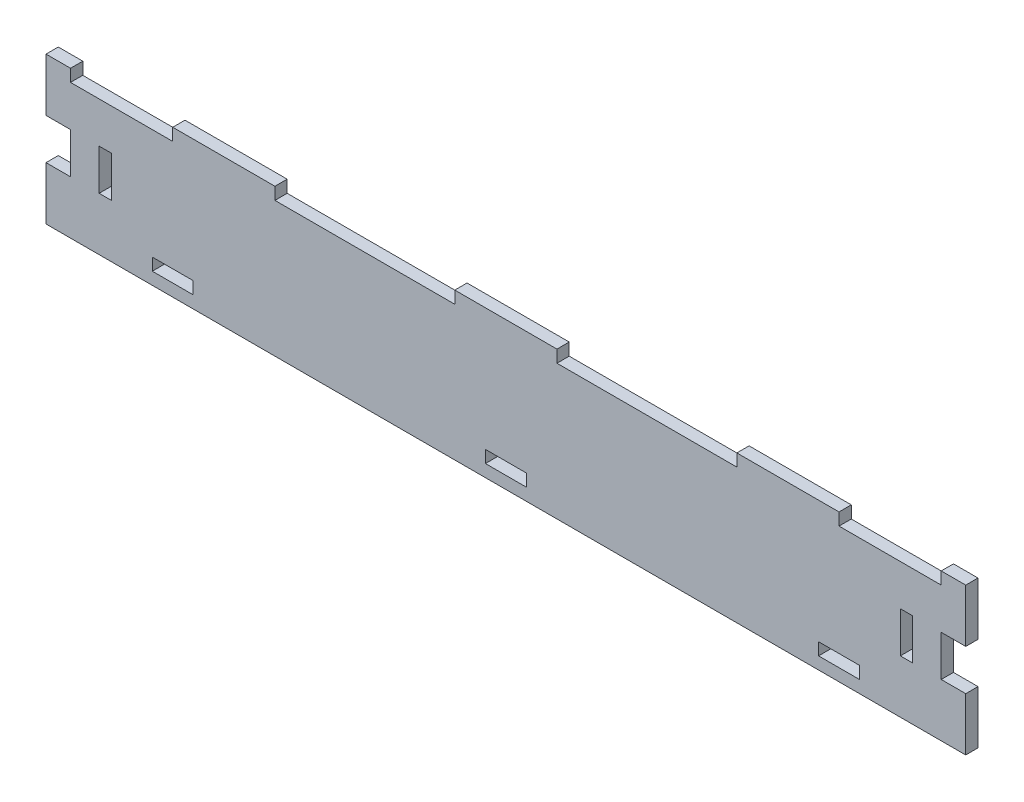
SolidWorks part; units mm, degrees
ref_plane "Спереди" through (0, 0, 0) normal (0, 0, 1) x (1, 0, 0)
ref_plane "Сверху" through (0, 0, 0) normal (0, 1, 0) x (1, 0, 0)
ref_plane "Справа" through (0, 0, 0) normal (1, 0, 0) x (0, 0, -1)
sketch "Эскиз1" plane through (0, 0, 0) normal (0, 0, 1) x (1, 0, 0)
  line L0 (0, 60) -> (0, 66)
  line L1 (0, 0) -> (450, 0) construction
  line L2 (0, 0) -> (0, 20)
  line L3 (12, 60) -> (62, 60)
  line L4 (450, 0) -> (450, 20)
  line L5 (0, 66) -> (12, 66)
  line L6 (12, 66) -> (12, 60)
  line L7 (62, 60) -> (62, 66)
  line L8 (62, 66) -> (112, 66)
  line L9 (112, 66) -> (112, 60)
  line L10 (200, 60) -> (200, 66)
  line L11 (200, 66) -> (250, 66)
  line L12 (250, 66) -> (250, 60)
  line L13 (338, 60) -> (338, 66)
  line L14 (338, 66) -> (388, 66)
  line L15 (388, 66) -> (388, 60)
  line L16 (438, 60) -> (438, 66)
  line L17 (438, 66) -> (450, 66)
  line L18 (450, 66) -> (450, 60)
  line L19 (0, 66) -> (450, 66) construction
  line L20 (112, 60) -> (200, 60)
  line L21 (250, 60) -> (338, 60)
  line L22 (388, 60) -> (438, 60)
  line L23 (0, 60) -> (450, 60) construction
  line L24 (52, 0) -> (52, 6)
  line L25 (52, 6) -> (72, 6)
  line L26 (72, 6) -> (72, 0)
  line L27 (215, 0) -> (215, 6)
  line L28 (215, 6) -> (235, 6)
  line L29 (235, 6) -> (235, 0)
  line L31 (378, 0) -> (378, 6)
  line L32 (378, 6) -> (398, 6)
  line L33 (398, 6) -> (398, 0)
  line L37 (-1058.3662, 6) -> (0, 6) construction
  line L38 (0, 20) -> (12, 20)
  line L39 (12, 20) -> (12, 40)
  line L40 (12, 40) -> (0, 40)
  line L41 (450, 20) -> (438, 20)
  line L42 (26, 20) -> (32, 20)
  line L43 (26, 20) -> (26, 40)
  line L44 (26, 40) -> (32, 40)
  line L45 (32, 20) -> (32, 40)
  line L46 (438, 20) -> (438, 40)
  line L47 (438, 40) -> (450, 40)
  line L48 (0, 40) -> (0, 60)
  line L49 (424, 40) -> (418, 40)
  line L50 (424, 40) -> (424, 20)
  line L51 (424, 20) -> (418, 20)
  line L52 (418, 40) -> (418, 20)
  line L53 (450, 40) -> (450, 60)
  line L54 (378, 0) -> (398, 0)
  line L55 (52, 0) -> (72, 0)
  line L56 (0, 0) -> (0, -6)
  line L57 (0, -6) -> (450, -6)
  line L58 (450, 0) -> (450, -6)
  line L59 (215, 0) -> (235, 0)
  line L60 (52, 6) -> (432.9281, 6) construction
  point P62 (225, 0)
  point P63 (72, 3)
  point P64 (0, 0)
  dimension "D1" = 450
  dimension "D2" = 60
  dimension "D3" = 66
  dimension "D4" = 12
  dimension "D5" = 50
  dimension "D6" = 50
  dimension "D7" = 88
  dimension "D8" = 50
  dimension "D9" = 88
  dimension "D10" = 50
  dimension "D11" = 12
  dimension "D12" = 6
  dimension "D13" = 143
  dimension "D14" = 20
  dimension "D15" = 143
  dimension "D16" = 20
  dimension "D17" = 20
  dimension "D18" = 225
  dimension "D19" = 14
  dimension "D20" = 20
  dimension "D21" = 12
  dimension "D22" = 6
  dimension "D23" = 6
  dimension "D24" = 12
  dimension "D25" = 14
  dimension "D26" = 14
  dimension "D27" = 6
extrude "Бобышка-Вытянуть1" add sketch "Эскиз1" along normal blind 6
